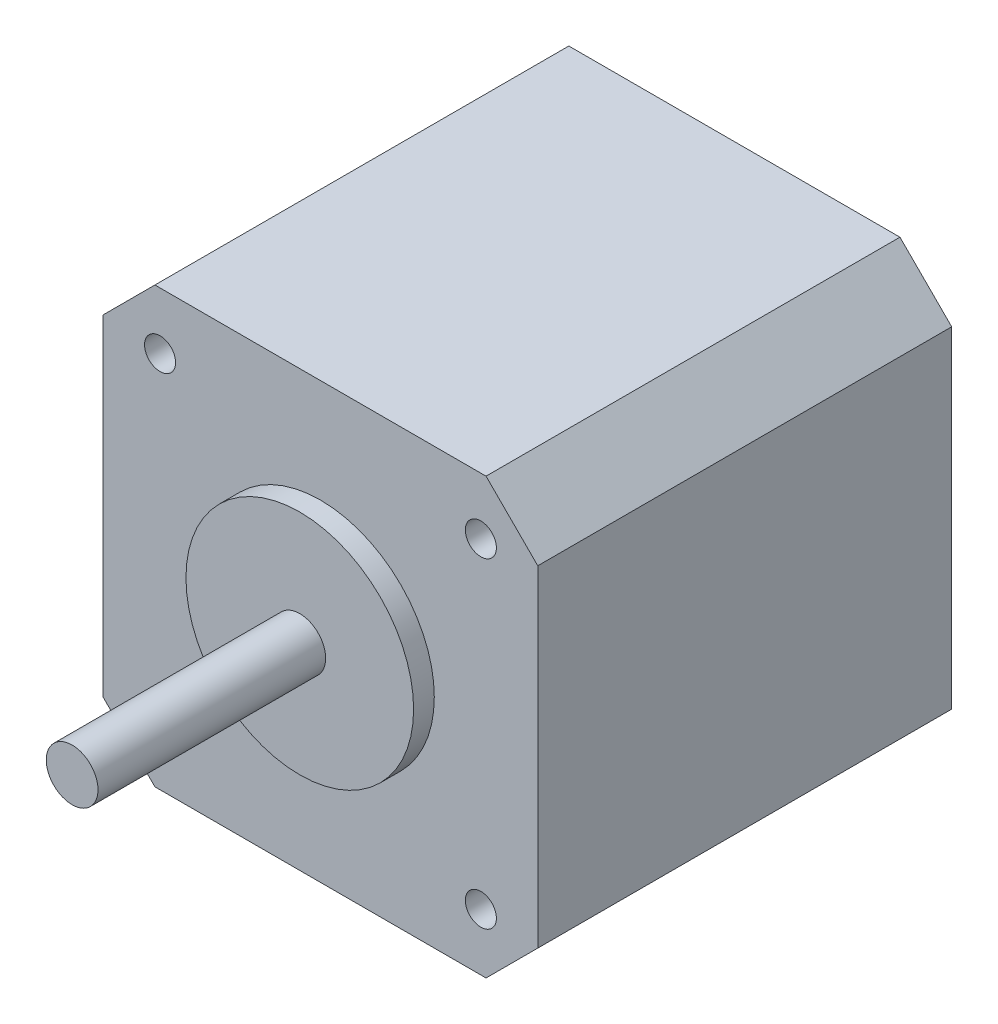
SolidWorks part; units mm, degrees
ref_plane "正面" through (0, 0, 0) normal (0, 0, 1) x (1, 0, 0)
ref_plane "平面" through (0, 0, 0) normal (0, 1, 0) x (1, 0, 0)
ref_plane "右側面" through (0, 0, 0) normal (1, 0, 0) x (0, 0, -1)
sketch "ｽｹｯﾁ1" plane through (0, 0, 0) normal (0, 0, 1) x (1, 0, 0)
  line L1 (-21, -21) -> (21, -21)
  line L2 (-21, -21) -> (-21, 21)
  line L3 (-21, 21) -> (21, 21)
  line L4 (21, -21) -> (21, 21)
  line L5 (-21, -21) -> (21, 21) construction
  line L6 (-21, 21) -> (21, -21) construction
  point P0 (0, 0)
  dimension "D1" = 42
  dimension "D2" = 42
extrude "ﾎﾞｽ - 押し出し1" add sketch "ｽｹｯﾁ1" along normal blind 40
sketch "ｽｹｯﾁ2" plane through (0, 0, 40) normal (0, 0, 1) x (1, 0, 0)
  circle A0 centre (0, 0) radius 11
  dimension "D1" = 22
extrude "ﾎﾞｽ - 押し出し2" add sketch "ｽｹｯﾁ2" along normal blind 2
sketch "ｽｹｯﾁ3" plane through (0, 0, 42) normal (0, 0, 1) x (1, 0, 0)
  circle A0 centre (0, 0) radius 2.5
  dimension "D1" = 5
extrude "ﾎﾞｽ - 押し出し5" add sketch "ｽｹｯﾁ3" along normal blind 22 contours A0
sketch "ｽｹｯﾁ4" plane through (0, 0, 40) normal (0, 0, 1) x (1, 0, 0)
  line L0 (-21, 0) -> (21, 0) construction
  line L1 (-21, 21) -> (-21, -21) construction
  line L2 (21, -21) -> (21, 21) construction
  line L3 (0, 21) -> (0, -21) construction
  line L4 (21, 21) -> (-21, 21) construction
  line L5 (-21, -21) -> (21, -21) construction
  circle A0 centre (-15.5, 15.5) radius 1.5
  circle A1 centre (15.5, 15.5) radius 1.5
  circle A2 centre (15.5, -15.5) radius 1.5
  circle A3 centre (-15.5, -15.5) radius 1.5
  dimension "D1" = 3
  dimension "D2" = 31
  dimension "D3" = 31
extrude "ｶｯﾄ - 押し出し1" cut sketch "ｽｹｯﾁ4" against normal blind 31.5
chamfer "面取り2" distance 5 angle 45 4 edges at (21, -21, 20) (-21, -21, 20) (21, 21, 20) (-21, 21, 20)
